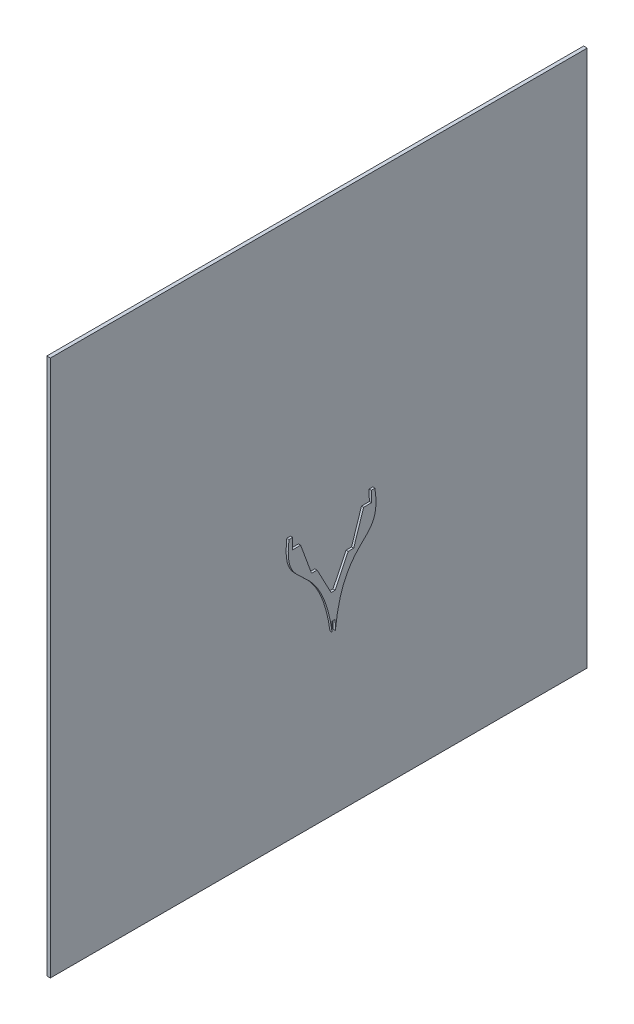
SolidWorks part; units mm, degrees
ref_plane "Plan de face" through (0, 0, 0) normal (0, 0, 1) x (1, 0, 0)
ref_plane "Plan de dessus" through (0, 0, 0) normal (0, 1, 0) x (1, 0, 0)
ref_plane "Plan de droite" through (0, 0, 0) normal (1, 0, 0) x (0, 0, -1)
sketch "Esquisse1" plane through (0, 0, 0) normal (0, 0, 1) x (1, 0, 0)
  point P0 (-20, 0)
  dimension "D1" = 20
sketch3d "Esquisse3D1"
  line L1 (-20, 1121.2893, 777.275) -> (-20, 1121.2893, -722.725)
  line L2 (-20, 1121.2893, 777.275) -> (-20, -378.7107, 777.275)
  line L3 (-20, -378.7107, 777.275) -> (-20, -378.7107, -722.725)
  line L4 (-20, 1121.2893, -722.725) -> (-20, -378.7107, -722.725)
  dimension "D1" = 1500
  dimension "D2" = 1500
extrude "Boss.-Extru.2" add sketch "Esquisse3D1" along direction (1, 0, 0) on the side of the normal blind 10 contours L2 L1 L4 L3
sketch "Esquisse4" plane through (-10, 0, 0) normal (1, 0, 0) x (0, 0, -1)
  line L0 (0, 0) -> (-7.701, 425.1082) construction
  line L1 (169.3944, 339.9131) -> (-188.5193, 333.4294) construction
  line L2 (-187.2006, 249.23) -> (169.0622, 255.6839) construction
  line L3 (-144.268, 175.2448) -> (126.4811, 180.1495) construction
sketch "Esquisse5" plane through (0, 0, 0) normal (1, 0, 0) x (0, 0, -1)
  line L0 (-7.701, 425.1082) -> (0, 0) construction
  line L1 (0, 0) -> (-7.701, 425.1082) construction
  line L2 (0, 0) -> (-0.7624, 42.0883) construction
  line L3 (-0.7624, 42.0883) -> (-6.1469, 339.3171) construction
  line L4 (-6.1469, 339.3171) -> (141.1806, 194.44) construction
  line L5 (141.1806, 194.44) -> (113.3474, 369.2014) construction
  line L8 (113.3474, 369.2014) -> (103.3474, 369.0202)
  line L9 (103.3474, 369.0202) -> (103.8349, 338.7255)
  line L10 (169.3944, 339.9131) -> (-188.5193, 333.4294) construction
  line L11 (103.8349, 338.7255) -> (81.9609, 338.3292)
  line L12 (81.9609, 338.3292) -> (54.2254, 253.6036)
  line L13 (-187.2006, 249.23) -> (169.0622, 255.6839) construction
  line L14 (54.2254, 253.6036) -> (38.9026, 253.326)
  line L15 (38.9026, 253.326) -> (2.4516, 177.9026)
  line L16 (-144.268, 175.2448) -> (126.4811, 180.1495) construction
  line L17 (2.4516, 177.9026) -> (-8.8934, 177.6971)
  line L18 (0, 0) -> (-0.7624, 42.0883) construction
  line L19 (-0.7624, 42.0883) -> (-6.1469, 339.3171) construction
  line L20 (-6.1469, 339.3171) -> (-148.1304, 189.199) construction
  line L21 (-148.1304, 189.199) -> (-126.6451, 364.8538) construction
  line L22 (-48.0523, 251.7508) -> (-8.8934, 177.6971)
  line L23 (-63.375, 251.4732) -> (-48.0523, 251.7508)
  line L24 (-94.161, 335.1387) -> (-63.375, 251.4732)
  line L25 (-116.035, 334.7425) -> (-94.161, 335.1387)
  line L26 (-116.6451, 365.035) -> (-116.035, 334.7425)
  line L27 (-126.6451, 364.8538) -> (-116.6451, 365.035)
  spline S0 degree 4 poles (0, 0) (-0.7624, 42.0883) (-6.1469, 339.3171) (141.1806, 194.44) (113.3474, 369.2014) knots 0 0 0 0 0 1 1 1 1 1
  spline S1 degree 4 poles (0, 0) (-0.7624, 42.0883) (-6.1469, 339.3171) (-148.1304, 189.199) (-126.6451, 364.8538) knots 0 0 0 0 0 1 1 1 1 1
  point P30 (-3.2209, 177.7999)
  dimension "D1" = 10
extrude "Boss.-Extru.3" add sketch "Esquisse5" along normal blind 6 separate body
sketch "Esquisse6" plane through (6, 0, 0) normal (1, 0, 0) x (0, 0, -1)
  line L0 (-5.9505, 79.9871) -> (-6.4396, 106.9871)
  line L1 (-6.4396, 106.9871) -> (2.5604, 107.1501)
  line L2 (2.5604, 107.1501) -> (3.0495, 80.1501)
  line L3 (3.0495, 80.1501) -> (117.0633, -47.527)
  line L4 (117.0633, -47.527) -> (-85.2277, -65.22)
  line L5 (-85.2277, -65.22) -> (-5.9505, 79.9871)
  line L6 (-5.9505, 79.9871) -> (3.0495, 80.1501) construction
  line L7 (-144.268, 175.2448) -> (126.4811, 180.1495) construction
  spline S0 degree 4 poles (-126.6451, 364.8538) (-148.1304, 189.199) (-6.1469, 339.3171) (-0.7624, 42.0883) (0, 0) knots 0 0 0 0 0 1 1 1 1 1 construction
  spline S1 degree 4 poles (0, 0) (-0.7624, 42.0883) (-6.1469, 339.3171) (141.1806, 194.44) (113.3474, 369.2014) knots 0 0 0 0 0 1 1 1 1 1 construction
  dimension "D1" = 9
  dimension "D2" = 27
extrude "Enlèv. mat.-Extru.1" cut sketch "Esquisse6" against normal blind 6
